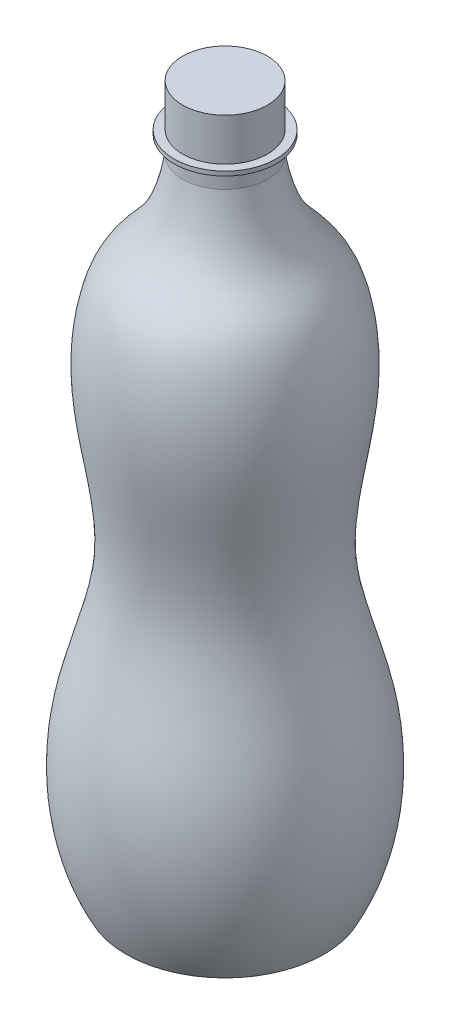
SolidWorks part; units mm, degrees
ref_plane "Alzado" through (0, 0, 0) normal (0, 0, 1) x (1, 0, 0)
ref_plane "Planta" through (0, 0, 0) normal (0, 1, 0) x (1, 0, 0)
ref_plane "Vista lateral" through (0, 0, 0) normal (1, 0, 0) x (0, 0, -1)
sketch "Croquis1" plane through (0, 0, 0) normal (0, 0, 1) x (1, 0, 0)
  line L0 (0, 0) -> (0, 250) construction
  line L1 (0, 250) -> (-15, 250)
  line L2 (-15, 250) -> (-15, 235)
  line L3 (-15, 235) -> (-18, 235)
  line L4 (-18, 235) -> (-18, 233.5)
  line L5 (-18, 233.5) -> (-15, 233.5)
  line L6 (-15, 233.5) -> (-15, 227.2831)
  line L7 (-35, 0) -> (0, 0)
  line L8 (0, 0) -> (0, 250)
  spline S0 degree 3 poles (-15, 227.2831) (-16.278, 219.3054) (-19.4893, 206.2609) (-32.6843, 194.3232) (-38.5473, 176.7023) (-39.1627, 152.8646) (-33.5616, 127.4626) (-30.9907, 94.978) (-48.2417, 54.8634) (-44.557, 17.9897) (-35, 0) knots 0 0 0 0 0.105528 0.159808 0.221006 0.33501 0.459708 0.552192 0.743985 1 1 1 1
  point P10 (0, 0)
  dimension "D1" = 250
  dimension "D2" = 15
  dimension "D3" = 15
  dimension "D4" = 1.5
  dimension "D5" = 3
  dimension "D6" = 35
revolve "Revolución1" add sketch "Croquis1" angle 360 about L0
